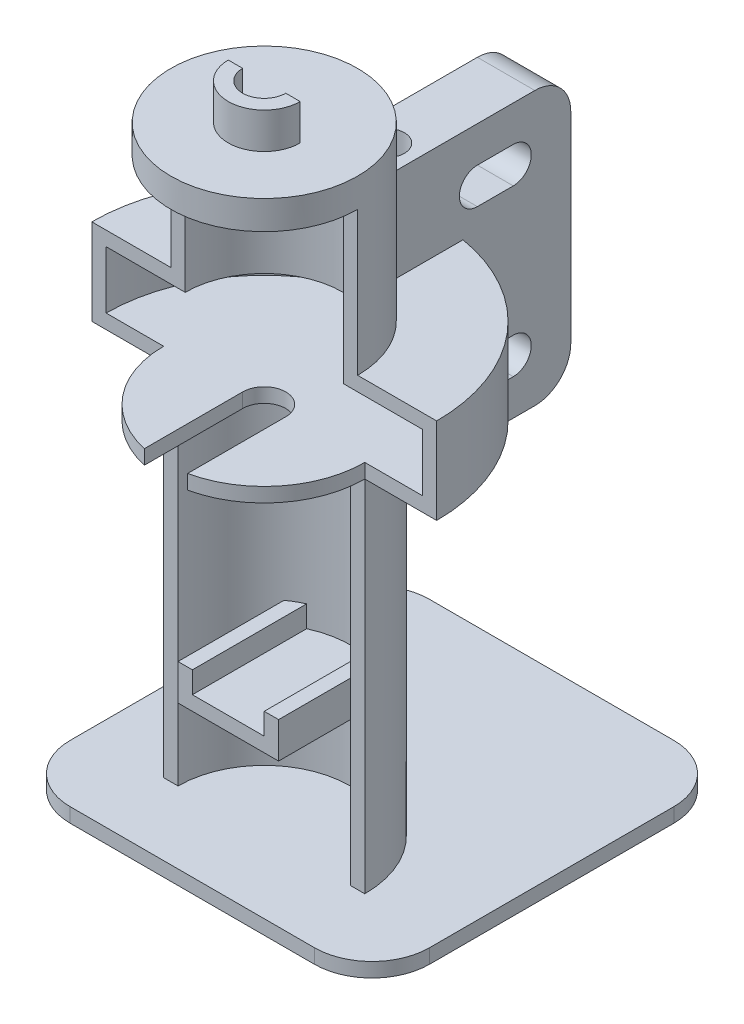
SolidWorks part; units mm, degrees
ref_plane "Front Plane" through (0, 0, 0) normal (0, 0, 1) x (1, 0, 0)
ref_plane "Top Plane" through (0, 0, 0) normal (0, 1, 0) x (1, 0, 0)
ref_plane "Right Plane" through (0, 0, 0) normal (1, 0, 0) x (0, 0, -1)
sketch "Sketch1" plane through (0, 0, 0) normal (0, 1, 0) x (1, 0, 0)
  line L0 (3, 0) -> (3, -13.6748)
  line L1 (-3, 0) -> (-3, -13.6748)
  line L2 (-14, 0) -> (-24, 0)
  line L3 (14, 0) -> (24, 0)
  circle A0 centre (0, 0) radius 14
  circle A1 centre (0, 0) radius 3
  arc A2 (24, 0) -> (-24, 0) centre (0, 0) ccw
  arc A3 (14, 0) -> (-14, 0) centre (0, 0) ccw
  dimension "D1" = 28
  dimension "D2" = 6
  dimension "D3" = 10
extrude "Motor-frontplate" add sketch "Sketch1" along normal blind 2 contours A1 L0 A0 L1 | L3 A2 L2 A3
sketch "Sketch2" plane through (0, 0, 0) normal (0, -1, 0) x (1, 0, 0)
  line L2 (-12, 0) -> (-14, 0)
  line L3 (12, 0) -> (14, 0)
  arc A1 (-14, 0) -> (14, 0) centre (0, 0) ccw
  arc A3 (14, 0) -> (3, 13.6748) centre (0, 0) ccw construction
  arc A4 (-12, 0) -> (12, 0) centre (0, 0) ccw
  dimension "D1" = 2
extrude "Motorkrybbe" add sketch "Sketch2" along normal blind 50 contours A4 L3 A1 L2
sketch "Sketch5" plane through (0, 2, 0) normal (0, 1, 0) x (1, 0, 0)
  line L0 (-24, 0) -> (-22, 0)
  line L1 (24, 0) -> (22, 0)
  arc A1 (24, 0) -> (-24, 0) centre (0, 0) ccw construction
  arc A2 (22, 0) -> (-22, 0) centre (0, 0) ccw
  arc A3 (22, 0) -> (-22, 0) centre (0, 0) ccw
  arc A4 (24, 0) -> (-24, 0) centre (0, 0) ccw
  dimension "D1" = 2
extrude "Skygge - Kappe" add sketch "Sketch5" along normal blind 8 contours A3 L0 A4 L1
sketch "Sketch6" plane through (0, 10, 0) normal (0, 1, 0) x (1, 0, 0)
  line L0 (-24, 0) -> (-11, 0)
  line L1 (11, 0) -> (24, 0)
  arc A0 (-11, 0) -> (11, 0) centre (0, 0) cw
  arc A1 (24, 0) -> (-24, 0) centre (0, 0) ccw construction
  arc A2 (24, 0) -> (-24, 0) centre (0, 0) ccw
  dimension "D1" = 11
extrude "Skygge - Topp" add sketch "Sketch6" along normal blind 2
sketch "Sketch7" plane through (0, 12, 0) normal (0, 1, 0) x (1, 0, 0)
  line L0 (-4, 12.3693) -> (-4, 23.6643)
  line L1 (4, 23.6643) -> (4, 12.3693)
  arc A0 (24, 0) -> (-24, 0) centre (0, 0) ccw construction
  arc A1 (11, 0) -> (-11, 0) centre (0, 0) ccw construction
  arc A2 (24, 0) -> (-24, 0) centre (0, 0) ccw
  arc A3 (11, 0) -> (-11, 0) centre (0, 0) ccw
  arc A4 (4, 12.3693) -> (-4, 12.3693) centre (0, 0) ccw
  arc A5 (4, 23.6643) -> (-4, 23.6643) centre (0, 0) ccw
  dimension "D3" = 2
  dimension "D1" = 4
  dimension "D2" = 4
extrude "LEDholder - Topp" add sketch "Sketch7" along normal blind 13 contours L1 A4 L0 A5
sketch "Sketch8" plane through (0, 0, 0) normal (0, -1, 0) x (1, 0, 0)
  line L0 (4, -23.6643) -> (4, -13.4164)
  line L1 (4, -23.6643) -> (4, -12.3693) construction
  line L2 (-4, -23.6643) -> (-4, -13.4164)
  line L3 (-4, -12.3693) -> (-4, -23.6643) construction
  arc A0 (-14, 0) -> (14, 0) centre (0, 0) ccw construction
  arc A1 (4, -13.4164) -> (-4.105, -13.3846) centre (0, 0) cw
  arc A2 (4, -23.6643) -> (-4, -23.6643) centre (0, 0) cw
  arc M1 (14, 0) -> (-14, 0) centre (0, 0) cw
  arc M3 (-24, 0) -> (24, 0) centre (0, 0) ccw
extrude "LEDholder - Bunn" add sketch "Sketch8" along normal blind 13 contours L2 L0 M3 M1
sketch "Sketch10" plane through (0, -13, 0) normal (0, -1, 0) x (1, 0, 0)
  line L2 (0, 0) -> (0, -14)
  line L3 (0, -14) -> (0, -14.5)
  line L4 (0, -14.5) -> (0, -17)
  arc A0 (-4, -13.4164) -> (4, -13.4164) centre (0, 0) ccw construction
  arc A1 (-4, -13.4164) -> (4, -13.4164) centre (0, 0) ccw
  circle A3 centre (0, -17) radius 2.5
  dimension "D1" = 5
  dimension "D2" = 0.5
extrude "LEDhull" cut sketch "Sketch10" against normal through all
sketch "Sketch11" plane through (0, 12, 0) normal (0, 1, 0) x (1, 0, 0)
  line L0 (-24, 0) -> (-11, 0) construction
  line L1 (11, 0) -> (24, 0) construction
  line L2 (-13, 0) -> (-11, 0)
  line L3 (13, 0) -> (11, 0)
  arc A0 (-11, 0) -> (11, 0) centre (0, 0) cw
  arc A1 (11, 0) -> (-11, 0) centre (0, 0) ccw construction
  arc A2 (-13, 0) -> (13, 0) centre (0, 0) cw
  dimension "D1" = 2
extrude "Rotorkappe - Vegg" add sketch "Sketch11" along normal blind 20
sketch "Sketch12" plane through (0, 32, 0) normal (0, 1, 0) x (1, 0, 0)
  circle A0 centre (0, 0) radius 13
extrude "Laserholder" add sketch "Sketch12" along normal blind 4
hole_wizard "Laser - hull" positions "Sketch13" profile "Sketch15" hole size "Ø6.0" standard "ISO" end condition up to next
sketch "Sketch13" plane through (0, 36, 0) normal (0, 1, 0) x (1, 0, 0)
  point P0 (0, 0)
sketch "Sketch15" plane through (0, 36, 0) normal (1, 0, 0) x (0, 0, 1)
  line L0 (0, 0) -> (0, 4)
  line L1 (0, 4) -> (3, 4)
  line L2 (3, 4) -> (3, 0)
  line L5 (3, 0) -> (0, 0)
  line L11 (0, -6.35) -> (0, 107.95) construction
  dimension "Thru Hole Dia." = 6
  dimension "Thru Hole Depth" = 4
sketch "Sketch16" plane through (0, -50, 0) normal (0, -1, 0) x (1, 0, 0)
  line L1 (-17, -40) -> (17, -40)
  line L2 (-25, -32) -> (-25, 2)
  line L3 (-17, 10) -> (17, 10)
  line L4 (25, -32) -> (25, 2)
  arc A0 (-25, 2) -> (-17, 10) centre (-17, 2) cw
  arc A1 (-17, -40) -> (-25, -32) centre (-17, -32) cw
  arc A2 (17, -40) -> (25, -32) centre (17, -32) ccw
  arc A3 (17, 10) -> (25, 2) centre (17, 2) cw
  point P0 (0, 0)
  dimension "D3" = 8
  dimension "D1" = 10
  dimension "D2" = 25
  dimension "D4" = 50
  dimension "D5" = 50
extrude "Bunnplate" add sketch "Sketch16" along normal blind 2
sketch "Sketch19" plane through (0, 0, 0) normal (0, 0, 1) x (1, 0, 0)
  line L0 (0, -33) -> (-5, -33)
  line L9 (-5, -33) -> (-5, -30)
  line L10 (-5, -30) -> (-7, -30)
  line L11 (-7, -30) -> (-7, -35)
  line L12 (-7, -35) -> (0, -35)
  line L13 (0, -35) -> (0, -33)
  line L14 (0, 0) -> (0, -33) construction
  dimension "D1" = 30
  dimension "D2" = 2
  dimension "D3" = 3
  dimension "D4" = 2
  dimension "D5" = 5
extrude "Boss-Extrude12" add sketch "Sketch19" along normal blind 5 and the other way up to next
mirror "Mirror2" about plane through (0, -35, -40.002) normal (1, 0, 0) of "Boss-Extrude12"
sketch "Sketch20" plane through (0, 25, 0) normal (0, 1, 0) x (1, 0, 0)
  line L0 (4, 23.6643) -> (4, 38.6643)
  line L1 (4, 38.6643) -> (-4, 38.6643)
  line L2 (-4, 38.6643) -> (-4, 23.6643)
  arc A0 (4, 23.6643) -> (-4, 23.6643) centre (0, 0) ccw construction
  arc A1 (4, 23.6643) -> (-4, 23.6643) centre (0, 0) ccw
  dimension "D1" = 15
extrude "LED - kabelholder" add sketch "Sketch20" against normal blind 38
sketch "Sketch21" plane through (4, 0, 0) normal (1, 0, 0) x (0, 0, -1)
  line L0 (25.6643, 17.5) -> (30.6643, 17.5) construction
  line L1 (25.6643, 20) -> (30.6643, 20)
  line L2 (25.6643, 15) -> (30.6643, 15)
  line L3 (38.6643, -13) -> (38.6643, 25) construction
  line L4 (12.3693, 25) -> (38.6643, -13) construction
  line L5 (38.6643, 25) -> (12.3693, 25) construction
  line L6 (25.5168, 6) -> (38.6643, 6)
  line L7 (25.6643, -5.5) -> (30.6643, -5.5) construction
  line L8 (25.6643, -8) -> (30.6643, -8)
  line L9 (25.6643, -3) -> (30.6643, -3)
  arc A0 (25.6643, 20) -> (25.6643, 15) centre (25.6643, 17.5) ccw
  arc A1 (30.6643, 15) -> (30.6643, 20) centre (30.6643, 17.5) ccw
  arc A2 (25.6643, -8) -> (25.6643, -3) centre (25.6643, -5.5) cw
  arc A3 (30.6643, -3) -> (30.6643, -8) centre (30.6643, -5.5) cw
  point P2 (28.1643, 17.5)
  point P19 (28.1643, -5.5)
  dimension "D1" = 8
  dimension "D2" = 5
  dimension "D3" = 5
  dimension "D4" = 5
extrude "Kabelholder - hull" cut sketch "Sketch21" against normal up to next contours L2 A1 L1 A0 | A3 L9 A2 L8
fillet "Fillet1" radius 5 2 edges at (0, 25, -38.6643) (0, -13, -38.6643)
sketch "Sketch22" plane through (0, 36, 0) normal (0, 1, 0) x (1, 0, 0)
  line L0 (-3, 0) -> (-5, 0)
  line L1 (3, 0) -> (5, 0)
  circle A1 centre (0, 0) radius 3 construction
  arc A2 (3, 0) -> (-3, 0) centre (0, 0) cw
  arc A3 (5, 0) -> (-5, 0) centre (0, 0) cw
  dimension "D1" = 2
extrude "Boss-Extrude14" add sketch "Sketch22" along normal blind 5
